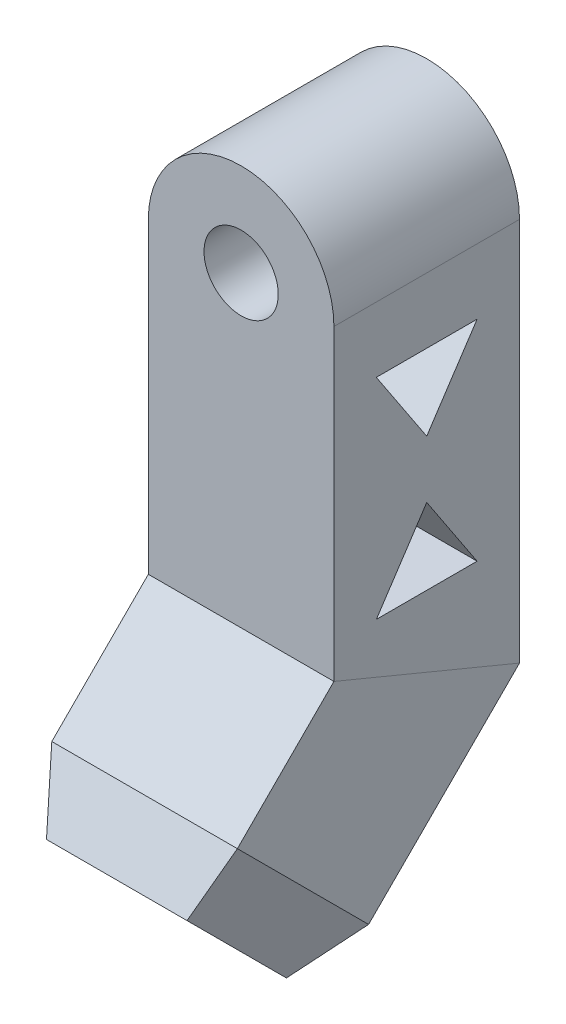
SolidWorks part; units mm, degrees
ref_plane "Front Plane" through (0, 0, 0) normal (0, 0, 1) x (1, 0, 0)
ref_plane "Top Plane" through (0, 0, 0) normal (0, 1, 0) x (1, 0, 0)
ref_plane "Right Plane" through (0, 0, 0) normal (1, 0, 0) x (0, 0, -1)
ref_plane "Plane2" through (0, 96.393, 0) normal (0, 1, 0) x (1, 0, 0)
sketch "Sketch10" plane through (0, 0, 0) normal (1, 0, 0) x (0, 0, -1)
  line L0 (0, 96.393) -> (0, 25.4)
  line L1 (55, 96.393) -> (-55, 96.393) construction
  line L2 (0, 25.4) -> (-25.4, 0)
  line L3 (55, 0) -> (-55, 0) construction
  dimension "D1" = 70.993
  dimension "D2" = 135
sketch "Sketch11" plane through (0, 96.393, 0) normal (0, 1, 0) x (1, 0, 0)
  line L1 (-19.05, -19.05) -> (19.05, -19.05)
  line L2 (-19.05, -19.05) -> (-19.05, 19.05)
  line L3 (-19.05, 19.05) -> (19.05, 19.05)
  line L4 (19.05, -19.05) -> (19.05, 19.05)
  line L5 (-19.05, -19.05) -> (19.05, 19.05) construction
  line L6 (-19.05, 19.05) -> (19.05, -19.05) construction
  point P0 (0, 0)
  dimension "D1" = 38.1
sweep "Sweep1" add profiles "Sketch11" path "Sketch10"
sketch "Sketch12" plane through (0, -12.7, 12.7) normal (0, -0.7071, 0.7071) x (1, 0, 0)
  line L8 (19.05, -1.0895) -> (19.05, 37.0105)
  line L9 (19.05, 37.0105) -> (-19.05, 37.0105)
  line L10 (-19.05, 37.0105) -> (-19.05, -1.0895)
  line L11 (-19.05, -1.0895) -> (19.05, -1.0895)
  line L12 (19.05, -1.0895) -> (19.05, 37.0105)
  line L13 (19.05, 37.0105) -> (-19.05, 37.0105)
  line L14 (-19.05, 37.0105) -> (-19.05, -1.0895)
  line L15 (-19.05, -1.0895) -> (19.05, -1.0895)
  dimension "D1" = 0
extrude "Boss-Extrude5" add sketch "Sketch12" along normal blind 12.7 draft 20
sketch "Sketch13" plane through (0, 0, -19.05) normal (0, 0, -1) x (-1, 0, 0)
  line L0 (55, 96.393) -> (-55, 96.393) construction
  line L1 (0, 55) -> (0, -55) construction
  line L2 (-19.05, 96.393) -> (19.05, 96.393)
  arc A0 (19.05, 96.393) -> (-19.05, 96.393) centre (0, 96.393) ccw
  dimension "D1" = 38.1
extrude "Boss-Extrude6" add sketch "Sketch13" against normal up to surface (38.1 mm away) up to face at (0, 64.8419, 19.05)
sketch "Sketch14" plane through (0, 0, 19.05) normal (0, 0, 1) x (1, 0, 0)
  circle A0 centre (0, 96.393) radius 7.62
  arc A1 (19.05, 96.393) -> (-19.05, 96.393) centre (0, 96.393) ccw construction
  dimension "D1" = 15.24
extrude "Cut-Extrude2" cut sketch "Sketch14" against normal blind 38.1
sketch "Sketch15" plane through (0, -21.6803, 21.6803) normal (0, -0.7071, 0.7071) x (1, 0, 0)
  line L0 (0, -34.9977) -> (0, 34.9977) construction
  line L4 (-14.4276, 32.3881) -> (-14.4276, 3.5329) construction
  line L5 (-14.4276, 3.5329) -> (14.4276, 3.5329) construction
  line L8 (0, 32.3881) -> (0, 3.5329) construction
  line L9 (14.4276, 32.3881) -> (-14.4276, 32.3881) construction
  circle A0 centre (0, 17.9605) radius 12.065
  point P12 (-14.4276, 17.9605)
  dimension "D1" = 24.13
extrude "Cut-Extrude3" cut sketch "Sketch15" against normal blind 12.7
sketch "Sketch16" plane through (-19.05, 0, 0) normal (-1, 0, 0) x (0, 0, 1)
  line L3 (-19.05, 61.4842) -> (19.05, 61.4842) construction
  line L4 (-10.3452, 83) -> (10.3452, 83)
  line L5 (10.3452, 83) -> (0, 67.3767)
  line L13 (-19.05, 96.393) -> (-19.05, 17.5092) construction
  line L14 (19.05, 96.393) -> (19.05, 33.2908) construction
  line L18 (-10.3452, 83) -> (0, 67.3767)
  line L19 (10.3452, 39.9683) -> (0, 55.5917)
  line L20 (-10.3452, 39.9683) -> (10.3452, 39.9683)
  line L21 (-10.3452, 39.9683) -> (0, 55.5917)
  point P9 (0, 61.4842)
  dimension "D1" = 20.6903
  dimension "D2" = 56.489
  dimension "D3" = 67.3767
  dimension "D6" = 38.1
  dimension "D7" = 61.4842
extrude "Cut-Extrude4" cut sketch "Sketch16" against normal blind 38.1
